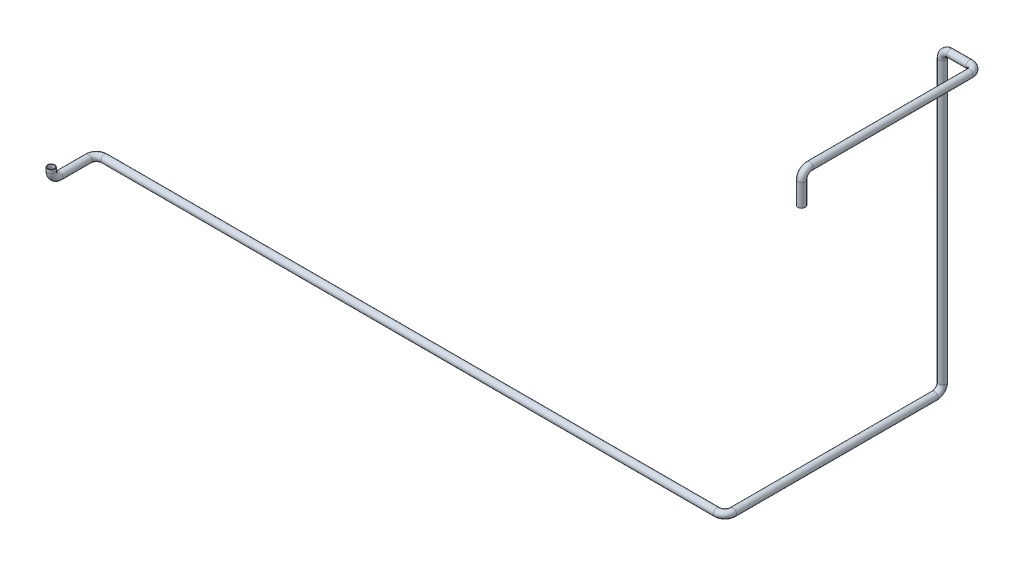
SolidWorks part; units mm, degrees
ref_plane "Alzado" through (0, 0, 0) normal (0, 0, 1) x (1, 0, 0)
ref_plane "Planta" through (0, 0, 0) normal (0, 1, 0) x (1, 0, 0)
ref_plane "Vista lateral" through (0, 0, 0) normal (1, 0, 0) x (0, 0, -1)
sketch "Croquis1" plane through (0, 0, 0) normal (0, 1, 0) x (1, 0, 0)
  circle A0 centre (0, 0) radius 12.7
  circle A1 centre (0, 0) radius 14.5
  dimension "D1" = 25.4
  dimension "D2" = 29
extrude "Saliente-Extruir1" add sketch "Croquis1" against normal blind 5
sketch3d "Croquis3D1"
  line L0 (0, -5, 0) -> (0, -13, 0)
  line L1 (0, -5, 0) -> (0, 0, 0) construction
  line L2 (0, -45, -32) -> (0, -45, -148)
  line L3 (32, -45, -180) -> (2468, -45, -180)
  line L4 (2500, -45, -212) -> (2500, -45, -1013)
  line L5 (2500, -13, -1045) -> (2500, 1103, -1045)
  line L6 (2640, 1103, -345) -> (2640, 1015, -345)
  line L7 (2532, 1135, -1045) -> (2608, 1135, -1045)
  line L8 (2640, 1135, -1013) -> (2640, 1135, -377)
  arc A0 (0, -45, -148) -> (32, -45, -180) centre (32, -45, -148) ccw
  arc A1 (0, -13, 0) -> (0, -45, -32) centre (0, -13, -32) ccw
  arc A2 (2500, -45, -1013) -> (2500, -13, -1045) centre (2500, -13, -1013) ccw
  arc A3 (2468, -45, -180) -> (2500, -45, -212) centre (2468, -45, -212) ccw
  arc A4 (2608, 1135, -1045) -> (2640, 1135, -1013) centre (2608, 1135, -1013) ccw
  arc A5 (2500, 1103, -1045) -> (2532, 1135, -1045) centre (2532, 1103, -1045) ccw
  arc A6 (2640, 1135, -377) -> (2640, 1103, -345) centre (2640, 1103, -377) ccw
  point P13 (0, -45, -180)
  point P14 (32, -77, -148)
  point P17 (0, -45, 0)
  point P18 (32, -13, -32)
  point P21 (2500, -45, -1045)
  point P22 (2532, -13, -1013)
  point P25 (2500, -45, -180)
  point P26 (2468, -13, -212)
  point P29 (2640, 1135, -1045)
  point P30 (2608, 1103, -1013)
  point P33 (2500, 1135, -1045)
  point P34 (2532, 1103, -1077)
  point P37 (2640, 1135, -345)
  point P38 (2672, 1103, -377)
  dimension "D9" = 32
  dimension "D10" = 32
  dimension "D11" = 32
  dimension "D12" = 32
  dimension "D1" = 180
  dimension "D2" = 40
  dimension "D3" = 2500
  dimension "D6" = 140
  dimension "D4" = 865
  dimension "D5" = 1180
  dimension "D7" = 700
  dimension "D8" = 120
sketch "Croquis2" plane through (0, -5, 0) normal (0, -1, 0) x (1, 0, 0)
  circle A0 centre (0, 0) radius 12.7
  circle A1 centre (0, 0) radius 14.5
sweep "Barrer1" add profiles "Croquis2" path "Croquis3D1"
